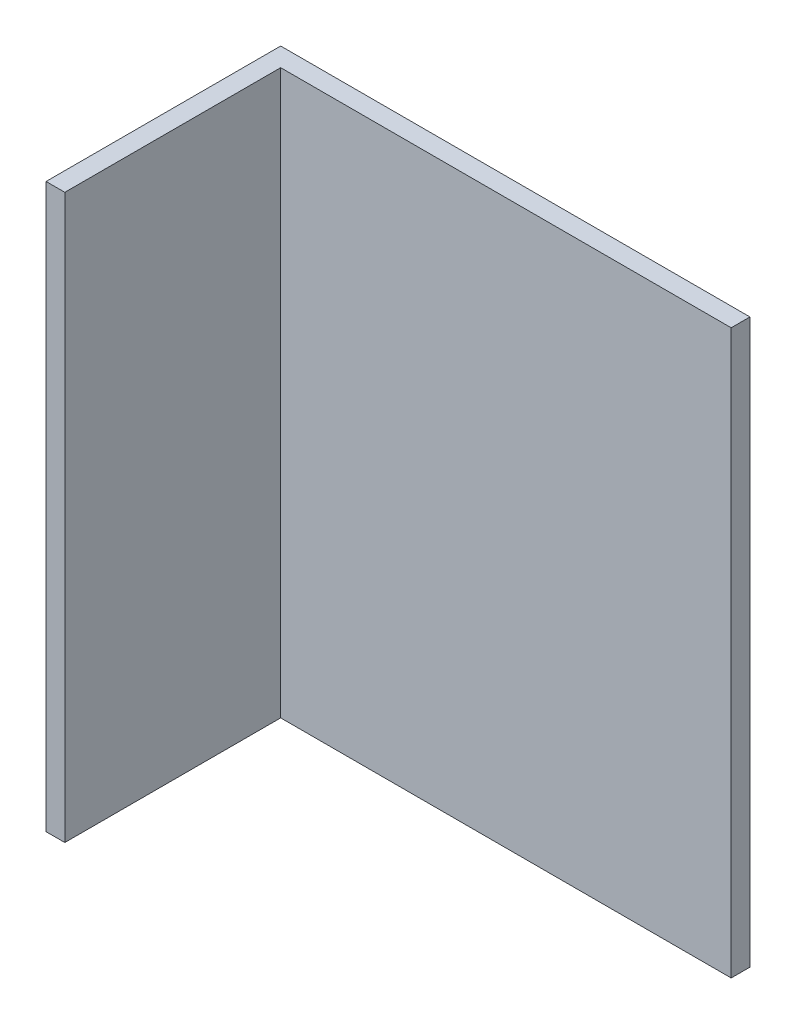
SolidWorks part; units mm, degrees
ref_plane "前视" through (0, 0, 0) normal (0, 0, 1) x (1, 0, 0)
ref_plane "上视" through (0, 0, 0) normal (0, 1, 0) x (1, 0, 0)
ref_plane "右视" through (0, 0, 0) normal (1, 0, 0) x (0, 0, -1)
sketch "草图1" plane through (0, 0, 0) normal (0, 0, 1) x (1, 0, 0)
  line L0 (160, 281.9635) -> (160, -120.4694) construction
  line L1 (0, 0) -> (200, 0)
  line L2 (0, 0) -> (0, 240)
  line L3 (0, 240) -> (200, 240)
  line L4 (200, 0) -> (200, 240)
  circle A0 centre (160, 40) radius 13
  circle A1 centre (160, 120) radius 13
  circle A2 centre (160, 200) radius 13
  dimension "D7" = 26
  dimension "D1" = 240
  dimension "D2" = 200
  dimension "D3" = 160
  dimension "D4" = 40
  dimension "D5" = 80
  dimension "D6" = 80
extrude "基体-拉伸" add sketch "草图1" along normal blind 8
sketch "草图2" plane through (0, 0, 8) normal (0, 0, 1) x (1, 0, 0)
  line L1 (0, 240) -> (8, 240)
  line L2 (0, 240) -> (0, 0)
  line L3 (0, 0) -> (8, 0)
  line L4 (8, 240) -> (8, 0)
  dimension "D1" = 8
extrude "凸台-拉伸1" add sketch "草图2" along normal blind 92
sketch "草图3" plane through (0, 0, 0) normal (-1, 0, 0) x (0, 0, 1)
  line L0 (52, 245.7913) -> (52, 32.4579) construction
  line L1 (0, 240) -> (0, 0) construction
  line L2 (100, 240) -> (0, 240) construction
  circle A0 centre (52, 200) radius 13
  circle A1 centre (52, 120) radius 13
  circle A2 centre (52, 40) radius 13
  dimension "D5" = 26
  dimension "D1" = 52
  dimension "D2" = 40
  dimension "D3" = 80
  dimension "D4" = 80
extrude "切除-拉伸1" cut sketch "草图3" against normal through all
sketch "草图5" plane through (0, 0, 8) normal (0, 0, 1) x (1, 0, 0)
  line L1 (200, 240) -> (8, 240)
  line L2 (200, 240) -> (200, 0)
  line L3 (200, 0) -> (8, 0)
  line L4 (8, 240) -> (8, 0)
extrude "凸台-拉伸2" add sketch "草图5" against normal blind 8
sketch "草图6" plane through (8, 0, 0) normal (1, 0, 0) x (0, 0, -1)
  line L1 (-100, 240) -> (-8, 240)
  line L2 (-100, 240) -> (-100, 0)
  line L3 (-100, 0) -> (-8, 0)
  line L4 (-8, 240) -> (-8, 0)
extrude "凸台-拉伸3" add sketch "草图6" against normal blind 8
